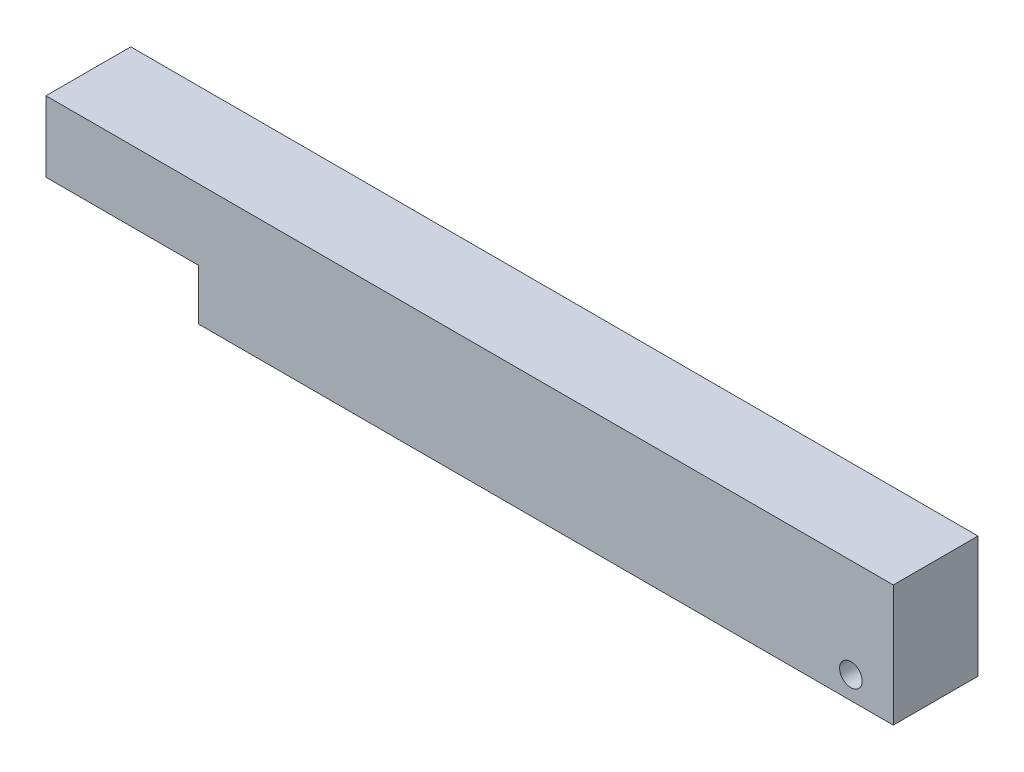
SolidWorks part; units mm, degrees
ref_plane "Plan de face" through (0, 0, 0) normal (0, 0, 1) x (1, 0, 0)
ref_plane "Plan de dessus" through (0, 0, 0) normal (0, 1, 0) x (1, 0, 0)
ref_plane "Plan de droite" through (0, 0, 0) normal (1, 0, 0) x (0, 0, -1)
sketch "Esquisse1" plane through (0, 0, 0) normal (0, 0, 1) x (1, 0, 0)
  line L1 (0, 0) -> (300, 0)
  line L2 (0, 0) -> (0, 25)
  line L3 (0, 25) -> (300, 25)
  line L4 (300, 0) -> (300, 25)
  dimension "D1" = 25
  dimension "D2" = 300
extrude "Boss.-Extru.1" add sketch "Esquisse1" along normal blind 30
sketch "Esquisse3" plane through (0, 0, 30) normal (0, 0, 1) x (1, 0, 0)
  line L0 (0, 0) -> (300, 0) construction
  line L1 (54, 0) -> (300, 0)
  line L2 (54, 0) -> (54, -18)
  line L3 (54, -18) -> (300, -18)
  line L4 (300, 0) -> (300, -18)
  line L5 (300, 0) -> (300, 25) construction
  line L6 (0, 25) -> (0, 0) construction
  dimension "D1" = 54
  dimension "D2" = 18
extrude "Boss.-Extru.2" add sketch "Esquisse3" against normal up to vertex (30 mm away)
sketch "Esquisse2" plane through (0, 0, 30) normal (0, 0, 1) x (1, 0, 0)
  line L0 (300, -10) -> (285, -10) construction
  line L3 (300, -18) -> (300, 25) construction
  line L5 (0, 0) -> (54, 0) construction
  circle A0 centre (285, -10) radius 4
  point P5 (279.104, -10)
  point P6 (300, -10)
  dimension "D1" = 8
  dimension "D3" = 10
  dimension "D2" = 15
extrude "Enlèv. mat.-Extru.1" cut sketch "Esquisse2" against normal through all both and the other way through all
